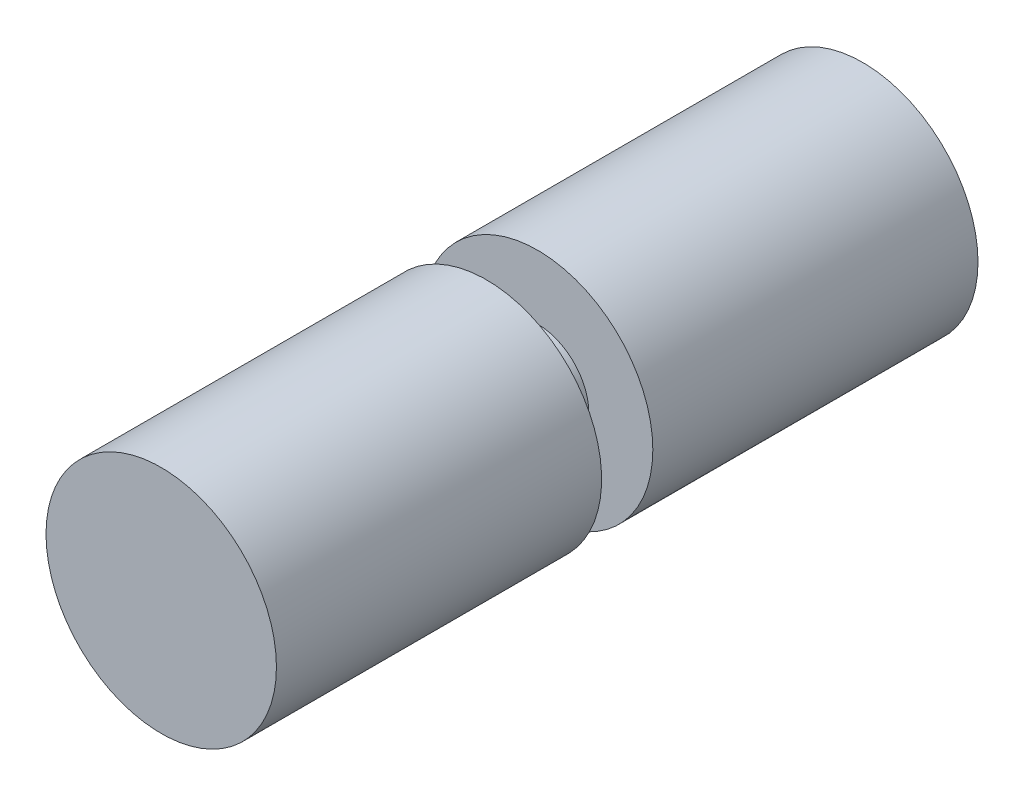
SolidWorks part; units mm, degrees
ref_plane "Front Plane" through (0, 0, 0) normal (0, 0, 1) x (1, 0, 0)
ref_plane "Top Plane" through (0, 0, 0) normal (0, 1, 0) x (1, 0, 0)
ref_plane "Right Plane" through (0, 0, 0) normal (1, 0, 0) x (0, 0, -1)
sketch "Sketch1" plane through (0, 0, 0) normal (0, 0, 1) x (1, 0, 0)
  circle A0 centre (0, 0) radius 22.5
  dimension "D1" = 45
extrude "Boss-Extrude1" add sketch "Sketch1" along normal blind 66
sketch "Sketch2" plane through (0, 0, 66) normal (0, 0, 1) x (1, 0, 0)
  circle A0 centre (0, 0) radius 10
  dimension "D1" = 20
extrude "Boss-Extrude2" add sketch "Sketch2" along normal blind 5
sketch "Sketch3" plane through (0, 0, 71) normal (0, 0, 1) x (1, 0, 0)
  circle A0 centre (0, 0) radius 22.5
  dimension "D1" = 45
extrude "Boss-Extrude3" add sketch "Sketch3" along normal blind 66
sketch "Sketch4" plane through (0, 0, 71) normal (0, 0, -1) x (-1, 0, 0)
  circle A0 centre (0, 0) radius 22.5
  circle A1 centre (0, 0) radius 10
  dimension "D1" = 20
extrude "Cut-Extrude2" cut sketch "Sketch4" against normal blind 2.5
sketch "Sketch5" plane through (0, 0, 66) normal (0, 0, 1) x (1, 0, 0)
  circle A1 centre (0, 0) radius 22.5
  circle A2 centre (0, 0) radius 22.5
  circle A3 centre (0, 0) radius 10
  circle A4 centre (0, 0) radius 10
  dimension "D1" = 0
  dimension "D2" = 0
extrude "Cut-Extrude3" cut sketch "Sketch5" against normal blind 2.5
